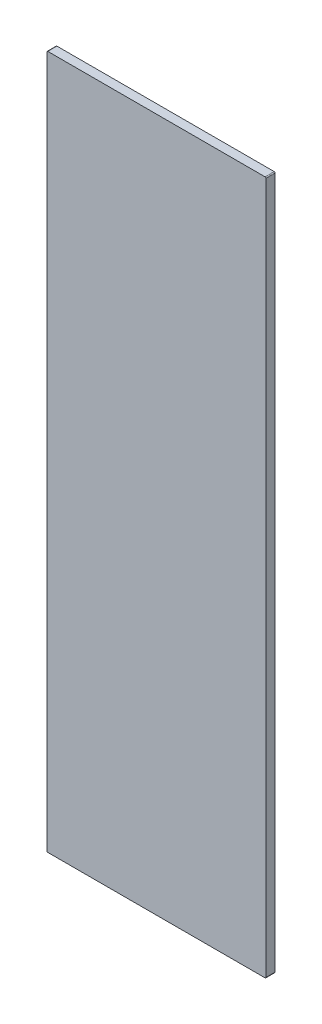
SolidWorks part; units mm, degrees
ref_plane "Front Plane" through (0, 0, 0) normal (0, 0, 1) x (1, 0, 0)
ref_plane "Top Plane" through (0, 0, 0) normal (0, 1, 0) x (1, 0, 0)
ref_plane "Right Plane" through (0, 0, 0) normal (1, 0, 0) x (0, 0, -1)
sketch "Sketch1" plane through (0, 0, 0) normal (0, 0, 1) x (1, 0, 0)
  line L0 (40, -760) -> (-40, -760) construction
  line L1 (199, 0) -> (-39, 0)
  line L2 (200, -1) -> (200, -759)
  line L3 (199, -760) -> (-39, -760)
  line L4 (-40, -1) -> (-40, -759)
  line L5 (-40, -760) -> (-40, 0) construction
  arc A0 (-39, 0) -> (-40, -1) centre (-39, -1) ccw
  arc A1 (199, 0) -> (200, -1) centre (199, -1) cw
  arc A2 (200, -759) -> (199, -760) centre (199, -759) cw
  arc A3 (-39, -760) -> (-40, -759) centre (-39, -759) cw
  point P13 (200, 0)
  point P18 (-40, -760)
  dimension "D1" = 1
extrude "Boss-Extrude1" add sketch "Sketch1" along normal blind 10
